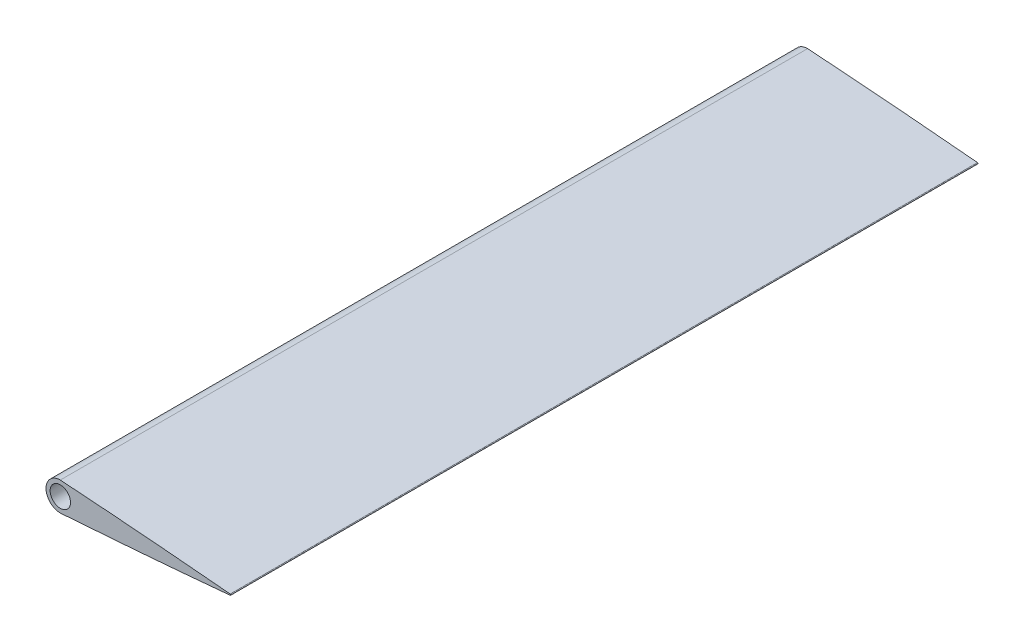
SolidWorks part; units mm, degrees
material "Foam"
ref_plane "Piano frontale" through (0, 0, 0) normal (0, 0, 1) x (1, 0, 0)
ref_plane "Piano superiore" through (0, 0, 0) normal (0, 1, 0) x (1, 0, 0)
ref_plane "Piano destro" through (0, 0, 0) normal (1, 0, 0) x (0, 0, -1)
curve "Curva1"
  spline degree 3 poles (100, 0.084, 0) (98.3335, 0.2367, 0) (95.0012, 0.5422, 0) (88.3356, 1.1109, 0) (80.0033, 1.7636, 0) (70.003, 2.4579, 0) (60.0031, 3.0617, 0) (50.003, 3.5521, 0) (40.0026, 3.9029, 0) (31.667, 4.0253, 0) (24.9992, 3.9769, 0) (19.9978, 3.845, 0) (14.9934, 3.5925, 0) (10.8272, 3.2377, 0) (7.4891, 2.814, 0) (4.9936, 2.4037, 0) (2.8496, 1.8679, 0) (1.1654, 1.321, 0) (-0.6646, 0, 0) (1.1654, -1.321, 0) (2.8496, -1.8679, 0) (4.9936, -2.4037, 0) (7.4891, -2.814, 0) (10.8272, -3.2377, 0) (14.9934, -3.5925, 0) (19.9978, -3.845, 0) (24.9992, -3.9769, 0) (31.667, -4.0253, 0) (40.0026, -3.9029, 0) (50.003, -3.5521, 0) (60.0031, -3.0617, 0) (70.003, -2.4579, 0) (80.0033, -1.7636, 0) (88.3356, -1.1109, 0) (95.0012, -0.5422, 0) (98.3335, -0.2367, 0) (100, -0.084, 0) knots 0 0 0 0 0.024876 0.049742 0.099443 0.149112 0.198751 0.248359 0.297937 0.347491 0.372267 0.397051 0.421859 0.446731 0.45922 0.471791 0.48456 0.491195 0.5 0.508805 0.51544 0.528209 0.54078 0.553269 0.578141 0.602949 0.627733 0.652509 0.702063 0.751641 0.801249 0.850888 0.900557 0.950258 0.975124 1 1 1 1
sketch "Schizzo2" plane through (0, 0, 0) normal (0, 0, 1) x (1, 0, 0)
  line L0 (75, 2.1072) -> (75, -2.1072) construction
  arc A0 (100, 0.084) -> (100, -0.084) centre (100, 0) cw
  arc A1 (75, 2.1072) -> (75, -2.1072) centre (75, 0) ccw
  spline S1 degree 3 poles (100, 0.084) (98.3335, 0.2367) (95.0012, 0.5422) (88.3356, 1.1109) (81.6686, 1.6332) (76.6669, 1.9915) (75, 2.1072) knots 0 0 0 0 0.024876 0.049742 0.099443 0.124282 0.124282 0.124282 0.124282
  spline S2 degree 3 poles (75, -2.1072) (76.6669, -1.9915) (81.6686, -1.6332) (88.3356, -1.1109) (95.0012, -0.5422) (98.3335, -0.2367) (100, -0.084) knots 0.875718 0.875718 0.875718 0.875718 0.900557 0.950258 0.975124 1 1 1 1
  spline S3 degree 3 poles (1265.2106, 6875.158) (458.4991, -96.3936) (277.9953, -15.0713) (88.3356, 1.1109) (80.0033, 1.7636) (70.003, 2.4579) (60.0031, 3.0617) (50.003, 3.5521) (40.0026, 3.9029) (31.667, 4.0253) (24.9992, 3.9769) (19.9978, 3.845) (14.9934, 3.5925) (10.8272, 3.2377) (7.4891, 2.814) (4.9936, 2.4037) (2.8496, 1.8679) (1.1654, 1.321) (-0.6646, 0) (1.1654, -1.321) (2.8496, -1.8679) (4.9936, -2.4037) (7.4891, -2.814) (10.8272, -3.2377) (14.9934, -3.5925) (19.9978, -3.845) (24.9992, -3.9769) (31.667, -4.0253) (40.0026, -3.9029) (50.003, -3.5521) (60.0031, -3.0617) (70.003, -2.4579) (80.0033, -1.7636) (88.3356, -1.1109) (277.9935, 15.0711) (458.4956, 96.392) (1265.1864, -6874.9491) knots -2.730056 -2.730056 -2.730056 -2.730056 0.024876 0.049742 0.099443 0.149112 0.198751 0.248359 0.297937 0.347491 0.372267 0.397051 0.421859 0.446731 0.45922 0.471791 0.48456 0.491195 0.5 0.508805 0.51544 0.528209 0.54078 0.553269 0.578141 0.602949 0.627733 0.652509 0.702063 0.751641 0.801249 0.850888 0.900557 0.950258 0.975124 3.730029 3.730029 3.730029 3.730029 only from (100, 0.084) to (100, -0.084) construction
  spline S4 degree 3 poles (100, 0.084) (98.3335, 0.2367) (95.0012, 0.5422) (88.3356, 1.1109) (80.0033, 1.7636) (70.003, 2.4579) (60.0031, 3.0617) (50.003, 3.5521) (40.0026, 3.9029) (31.667, 4.0253) (24.9992, 3.9769) (19.9978, 3.845) (14.9934, 3.5925) (10.8272, 3.2377) (7.4891, 2.814) (4.9936, 2.4037) (2.8496, 1.8679) (1.1654, 1.321) (-0.6646, 0) (1.1654, -1.321) (2.8496, -1.8679) (4.9936, -2.4037) (7.4891, -2.814) (10.8272, -3.2377) (14.9934, -3.5925) (19.9978, -3.845) (24.9992, -3.9769) (31.667, -4.0253) (40.0026, -3.9029) (50.003, -3.5521) (60.0031, -3.0617) (70.003, -2.4579) (80.0033, -1.7636) (88.3356, -1.1109) (95.0012, -0.5422) (98.3335, -0.2367) (100, -0.084) knots 0 0 0 0 0.024876 0.049742 0.099443 0.149112 0.198751 0.248359 0.297937 0.347491 0.372267 0.397051 0.421859 0.446731 0.45922 0.471791 0.48456 0.491195 0.5 0.508805 0.51544 0.528209 0.54078 0.553269 0.578141 0.602949 0.627733 0.652509 0.702063 0.751641 0.801249 0.850888 0.900557 0.950258 0.975124 1 1 1 1 construction
  dimension "D3" = 0.084
  dimension "D1" = 25
  dimension "D2" = 4.2144
extrude "Estrusione-Estrusione1" add sketch "Schizzo2" along normal blind 110 contours A1 S2 A0 S1
sketch "Schizzo3" plane through (0, 0, 110) normal (0, 0, 1) x (1, 0, 0)
  circle A0 centre (75, 0) radius 1.5
  dimension "D1" = 3
extrude "Taglio-Estrusione1" cut sketch "Schizzo3" against normal through all
